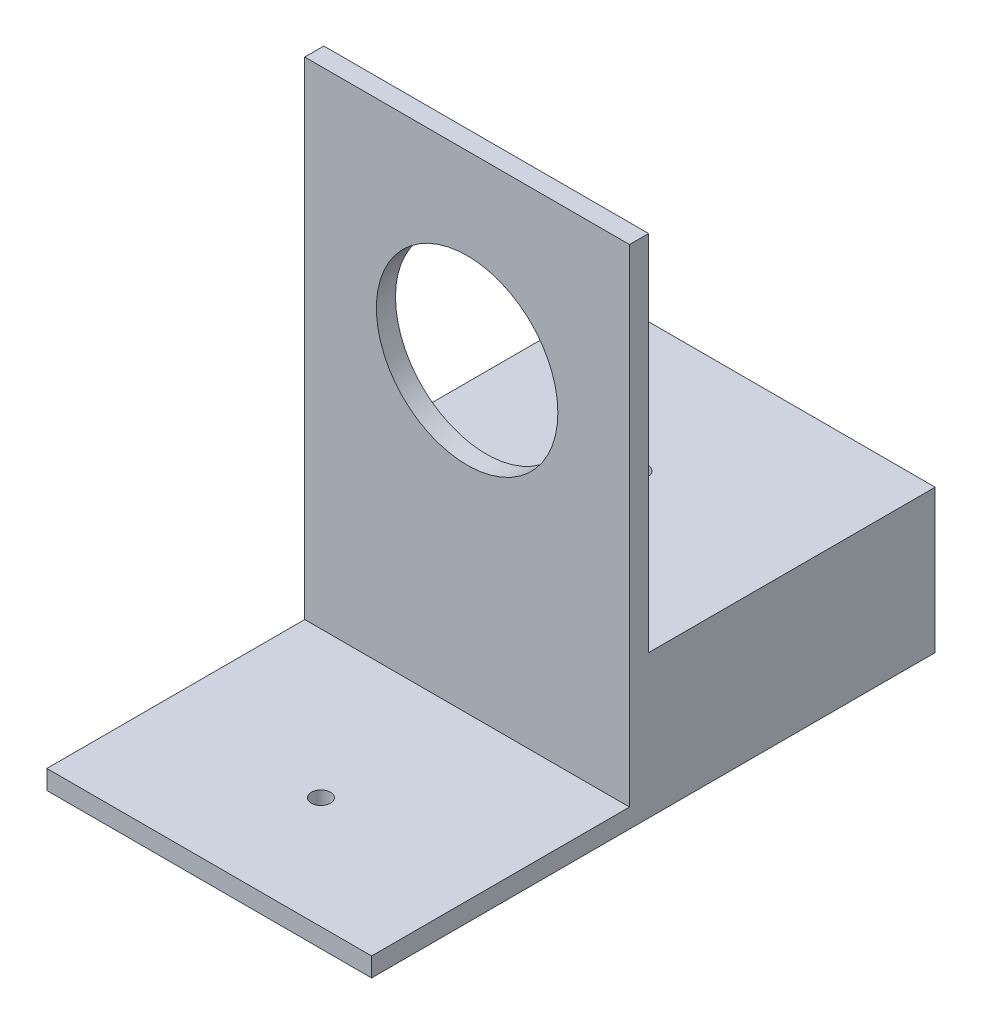
SolidWorks part; units mm, degrees
ref_plane "Front" through (0, 0, 0) normal (0, 0, 1) x (1, 0, 0)
ref_plane "Top" through (0, 0, 0) normal (0, 1, 0) x (1, 0, 0)
ref_plane "Right" through (0, 0, 0) normal (1, 0, 0) x (0, 0, -1)
sketch "Sketch1" plane through (0, 0, 0) normal (0, 0, 1) x (1, 0, 0)
  line L1 (0, 0) -> (34, 0)
  line L2 (0, 0) -> (0, 53)
  line L3 (0, 53) -> (34, 53)
  line L4 (34, 0) -> (34, 53)
  dimension "D1" = 53
  dimension "D2" = 34
extrude "Boss-Extrude1" add sketch "Sketch1" along normal blind 2
sketch "Sketch2" plane through (0, 0, 2) normal (0, 0, 1) x (1, 0, 0)
  line L0 (34, 0) -> (34, 53) construction
  line L1 (0, 0) -> (34, 0)
  line L2 (0, 0) -> (0, 2)
  line L3 (0, 2) -> (34, 2)
  line L4 (34, 0) -> (34, 2)
  dimension "D1" = 2
extrude "Boss-Extrude2" add sketch "Sketch2" along normal blind 27
sketch "Sketch3" plane through (0, 0, 0) normal (0, 0, -1) x (-1, 0, 0)
  line L0 (-34, 0) -> (-34, 53) construction
  line L1 (0, 0) -> (-34, 0)
  line L2 (0, 0) -> (0, 15)
  line L3 (0, 15) -> (-34, 15)
  line L4 (-34, 0) -> (-34, 15)
  dimension "D1" = 15
extrude "Boss-Extrude3" add sketch "Sketch3" along normal blind 30
sketch "Sketch4" plane through (0, 0, 2) normal (0, 0, 1) x (1, 0, 0)
  line L0 (17, -5.9529) -> (17, 59.0578) construction
  line L1 (0, 53) -> (0, 2) construction
  line L2 (34, 53) -> (0, 53) construction
  circle A0 centre (17, 34) radius 9.5
  dimension "D2" = 19
  dimension "D1" = 17
  dimension "D3" = 19
extrude "Cut-Extrude1" cut sketch "Sketch4" against normal through all contours A0
sketch "Sketch5" plane through (0, 0, 0) normal (0, -1, 0) x (-1, 0, 0)
  line L0 (-17, -29) -> (-17, 30) construction
  line L1 (0, -29) -> (-34, -29) construction
  line L2 (-34, 30) -> (0, 30) construction
hole_wizard "#94 (0.0071) Diameter Hole1" positions "Sketch7" profile "Sketch6" hole size "#94" standard "ANSI Inch" end condition through all
sketch "Sketch7" plane through (0, 0, 0) normal (0, -1, 0) x (-1, 0, 0)
  line L0 (-17, -29) -> (-17, 30) construction
  point P0 (-17, -17.3048)
  point P4 (-17, 15.9456)
sketch "Sketch6" plane through (17, 0, 17.3048) normal (1, 0, 0) x (0, 0, -1)
  line L0 (0, 0) -> (0, 53)
  line L1 (0, 53) -> (1, 53)
  line L2 (1, 53) -> (1, 0)
  line L5 (1, 0) -> (0, 0)
  line L11 (0, -6.35) -> (0, 107.95) construction
  dimension "Thru Hole Dia." = 2
  dimension "Thru Hole Depth" = 53
